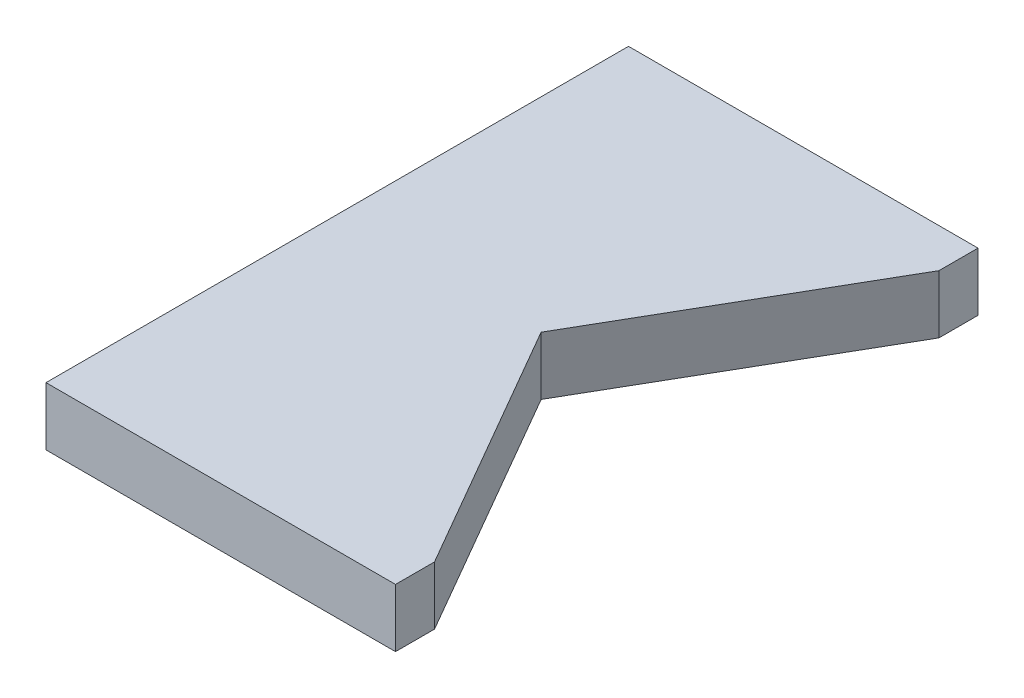
SolidWorks part; units mm, degrees
ref_plane "Front Plane" through (0, 0, 0) normal (0, 0, 1) x (1, 0, 0)
ref_plane "Top Plane" through (0, 0, 0) normal (0, 1, 0) x (1, 0, 0)
ref_plane "Right Plane" through (0, 0, 0) normal (1, 0, 0) x (0, 0, -1)
sketch "Sketch1" plane through (0, 0, 0) normal (0, 1, 0) x (1, 0, 0)
  line L0 (0, 0) -> (60, 0)
  line L1 (60, 0) -> (60, 6.7)
  line L2 (60, 6.7) -> (35, 50)
  line L3 (35, 50) -> (60, 93.3)
  line L4 (60, 93.3) -> (60, 100)
  line L5 (60, 100) -> (0, 100)
  line L6 (0, 100) -> (0, 0)
extrude "Boss-Extrude1" add sketch "Sketch1" along normal blind 10
